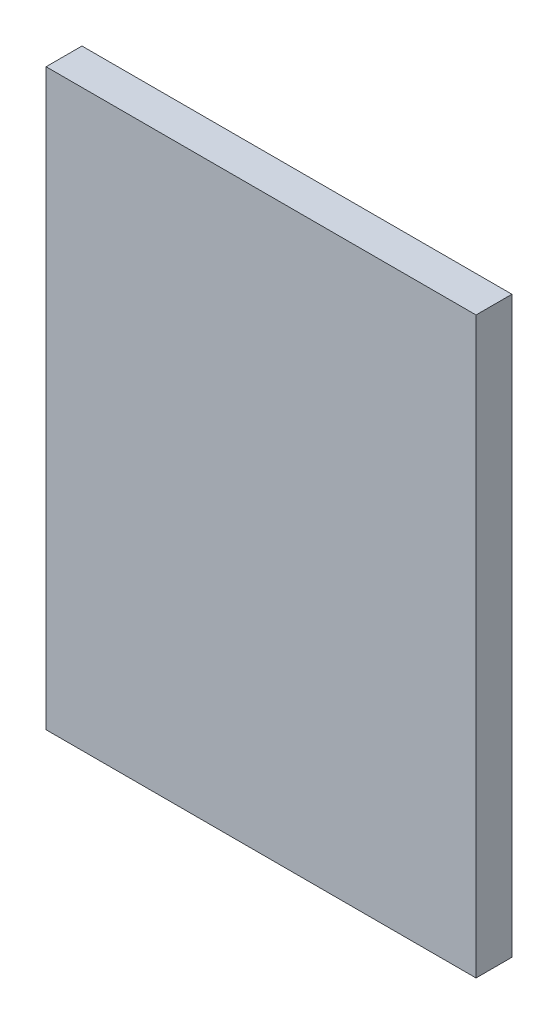
SolidWorks part; units mm, degrees
material "ABS PC"
ref_plane "X-Y Datum" through (0, 0, 0) normal (0, 0, 1) x (1, 0, 0)
ref_plane "X-Z Datum" through (0, 0, 0) normal (0, 1, 0) x (1, 0, 0)
ref_plane "Y-Z Datum" through (0, 0, 0) normal (1, 0, 0) x (0, 0, -1)
sketch "Sketch1" plane through (0, 0, 0) normal (0, 0, 1) x (1, 0, 0)
  line L1 (-38.0378, -50.8) -> (38.0378, -50.8)
  line L2 (-38.0378, -50.8) -> (-38.0378, 50.8)
  line L3 (-38.0378, 50.8) -> (38.0378, 50.8)
  line L4 (38.0378, -50.8) -> (38.0378, 50.8)
  line L5 (-38.0378, -50.8) -> (38.0378, 50.8) construction
  line L6 (-38.0378, 50.8) -> (38.0378, -50.8) construction
  point P0 (0, 0)
  dimension "D1" = 76.0755
  dimension "D2" = 101.6
extrude "Boss-Extrude1" add sketch "Sketch1" along normal blind 6.35
